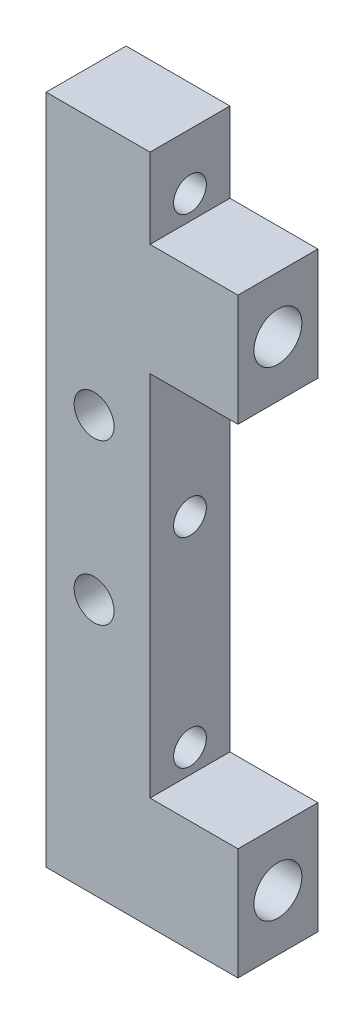
SolidWorks part; units mm, degrees
material "Alliage 1060"
ref_plane "Plan de face" through (0, 0, 0) normal (0, 0, 1) x (1, 0, 0)
ref_plane "Plan de dessus" through (0, 0, 0) normal (0, 1, 0) x (1, 0, 0)
ref_plane "Plan de droite" through (0, 0, 0) normal (1, 0, 0) x (0, 0, -1)
sketch "Esquisse1" plane through (0, 0, 0) normal (1, 0, 0) x (0, 0, -1)
  line L0 (0, -34.1319) -> (0, 34.1319) construction
  line L1 (-2.5, 21) -> (2.5, 21)
  line L2 (-2.5, 21) -> (-2.5, -21)
  line L3 (-2.5, -21) -> (2.5, -21)
  line L4 (2.5, 21) -> (2.5, -21)
  line L5 (-9.7842, 0) -> (12.9098, 0) construction
  circle A0 centre (0, -17.5) radius 1.5 construction
  circle A1 centre (0, 12.5) radius 1.5 construction
  circle A2 centre (0, -17.5) radius 1.5
  circle A3 centre (0, 12.5) radius 1.5
  dimension "D1" = 42
  dimension "D2" = 5
extrude "Extrusion1" add sketch "Esquisse1" along normal mid plane 12
hole_wizard "Trou taraudé M3x0.51" positions "Esquisse3" profile "Esquisse2" tap size "M3x0.5" standard "Ansi Métrique" end condition through all
sketch "Esquisse3" plane through (0, 0, -2.5) normal (0, 0, -1) x (-1, 0, 0)
  line L0 (6, -21) -> (6, 21) construction
  point P0 (3, 5)
  point P1 (3, -5)
  dimension "D2" = 5
  dimension "D3" = 5
  dimension "D4" = 3
sketch "Esquisse2" plane through (-3, 5, -2.5) normal (1, 0, 0) x (0, 1, 0)
  line L0 (0, 0) -> (0, 5)
  line L1 (0, 5) -> (1.25, 5)
  line L2 (1.25, 5) -> (1.25, 0)
  line L5 (1.25, 0) -> (0, 0)
  line L11 (0, -6.35) -> (0, 107.95) construction
  dimension "Diamètre du trou pour taraudage jusqu'au prochain" = 2.5
  dimension "Profondeur du trou pour taraudage jusqu'au prochain" = 5
cosmetic thread "Filetage de perçage1" parameters "D2"=3
cosmetic thread "Filetage de perçage2" parameters "D2"=3
sketch "Esquisse4" plane through (0, 0, -2.5) normal (0, 0, -1) x (-1, 0, 0)
  line L0 (6, 21) -> (-0.5, 21)
  line L1 (-6, 21) -> (6, 21) construction
  line L2 (-0.5, 21) -> (-0.5, 16)
  line L3 (-0.5, 16) -> (-6, 16)
  line L4 (-6, -21) -> (-6, 21) construction
  line L5 (-6, 16) -> (-6, 9)
  line L6 (-6, 9) -> (-0.5, 9)
  line L7 (-0.5, 9) -> (-0.5, -14)
  line L8 (-0.5, -14) -> (-6, -14)
  line L9 (-6, -14) -> (-6, -21)
  line L10 (-6, -21) -> (6, -21)
  line L11 (6, -21) -> (6, 21)
  line L12 (-35.5176, 16.5) -> (-35.5176, 8.5) construction
  line L14 (-30.5176, -13.5) -> (-30.5176, 8.5) construction
  line L15 (-30.5176, -13.5) -> (-35.5176, -13.5) construction
  line L16 (-35.5176, 8.5) -> (-30.5176, 8.5) construction
  line L17 (-30.5176, 16.5) -> (-35.5176, 16.5) construction
  dimension "D1" = 29.5176
  dimension "D2" = 5.5
  dimension "D3" = 30.0176
  dimension "D4" = 0.5
  dimension "D5" = 0.5
  dimension "D6" = 0.5
extrude "Enlèv. mat.-Extru.1" cut sketch "Esquisse4" against normal through all flip side to cut
hole_wizard "Trou taraudé M2.5x0.451" positions "Esquisse7" profile "Esquisse6" tap size "M2.5x0.45" standard "Ansi Métrique" end condition through all
sketch "Esquisse7" plane through (-6, 0, 0) normal (-1, 0, 0) x (0, 0, 1)
  point P0 (0, 17.5)
  point P1 (0, 0)
  point P3 (0, -12.5)
sketch "Esquisse6" plane through (-6, 17.5, 0) normal (0, 1, 0) x (0, 0, 1)
  line L0 (0, 0) -> (0, 12)
  line L1 (0, 12) -> (1.025, 12)
  line L2 (1.025, 12) -> (1.025, 0)
  line L5 (1.025, 0) -> (0, 0)
  line L11 (0, -6.35) -> (0, 107.95) construction
  dimension "Diamètre du trou pour taraudage jusqu'au prochain" = 2.05
  dimension "Profondeur du trou pour taraudage jusqu'au prochain" = 12
cosmetic thread "Filetage de perçage3" parameters "D2"=2.5
cosmetic thread "Filetage de perçage4" parameters "D2"=2.5
cosmetic thread "Filetage de perçage5" parameters "D2"=2.5
